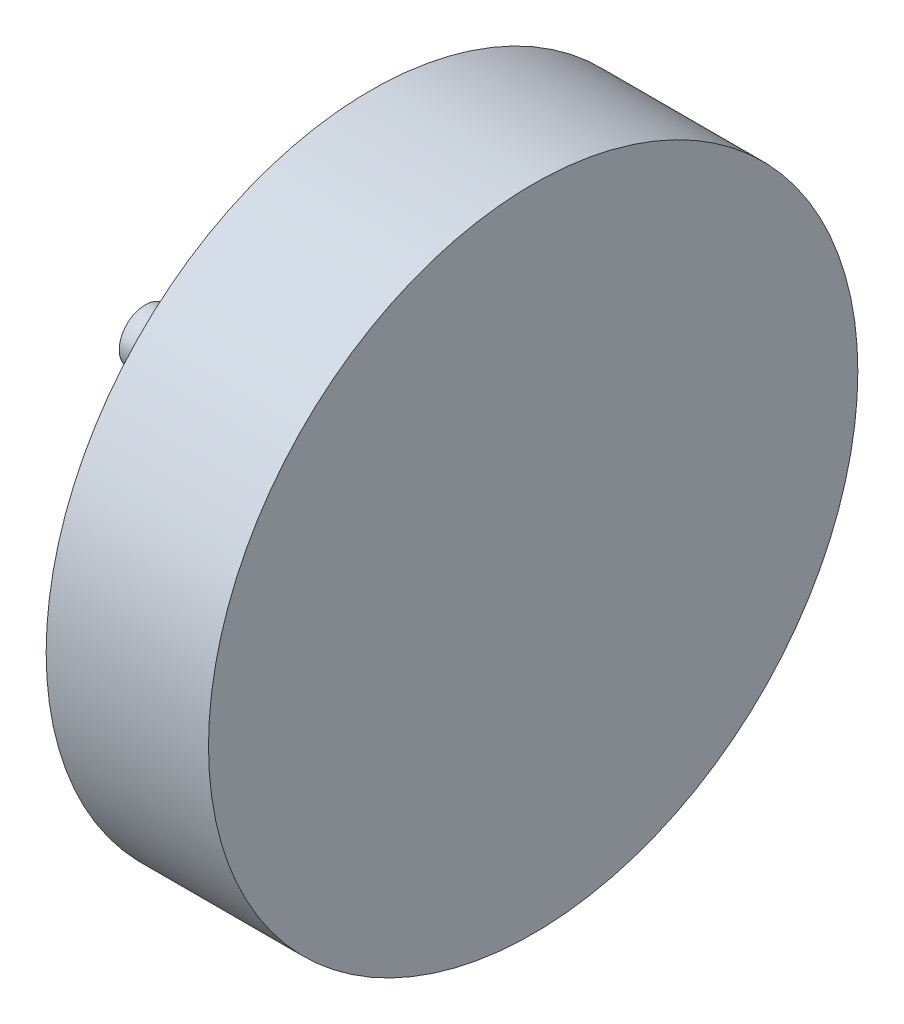
SolidWorks part; units mm, degrees
ref_plane "Front Plane" through (0, 0, 0) normal (0, 0, 1) x (1, 0, 0)
ref_plane "Top Plane" through (0, 0, 0) normal (0, 1, 0) x (1, 0, 0)
ref_plane "Right Plane" through (0, 0, 0) normal (1, 0, 0) x (0, 0, -1)
sketch "Sketch1" plane through (0, 0, 0) normal (0, 1, 0) x (1, 0, 0)
  line L0 (0, 0) -> (0, 252.75) construction
  line L1 (0, 252.75) -> (70.75, 252.75) construction
  point P3 (0, 0)
  dimension "D1" = 70.75
  dimension "D2" = 252.75
ref_plane "Plane1" through (70.75, 0, -252.75) normal (1, 0, 0) x (0, 0, -1)
sketch "Sketch2" plane through (70.75, 0, -252.75) normal (1, 0, 0) x (0, 0, -1)
  line L0 (-252.75, 0) -> (0, 0) construction
  circle A0 centre (0, 0) radius 50
  point P4 (14.7614, 0)
  dimension "D1" = 100
extrude "Boss-Extrude1" add sketch "Sketch2" against normal blind 25
sketch "Sketch3" plane through (70.75, 0, -252.75) normal (1, 0, 0) x (0, 0, -1)
  circle A0 centre (0, 0) radius 4
  circle A1 centre (0, 0) radius 50 construction
  dimension "D1" = 8
extrude "Boss-Extrude2" add sketch "Sketch3" against normal blind 59.75
